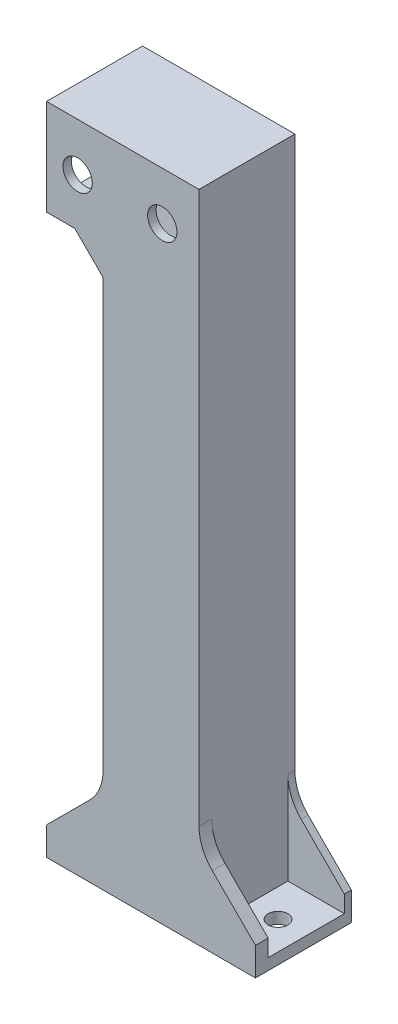
SolidWorks part; units mm, degrees
ref_plane "Front Plane" through (0, 0, 0) normal (0, 0, 1) x (1, 0, 0)
ref_plane "Top Plane" through (0, 0, 0) normal (0, 1, 0) x (1, 0, 0)
ref_plane "Right Plane" through (0, 0, 0) normal (1, 0, 0) x (0, 0, -1)
sketch "Sketch1" plane through (0, 0, 0) normal (0, 0, 1) x (1, 0, 0)
  line L0 (0, 18.3137) -> (0, 94)
  line L2 (17, 0) -> (0, 0)
  line L5 (27, 5) -> (27, 0)
  line L6 (27, 0) -> (17, 0)
  line L8 (-10, 5) -> (-10, 0)
  line L9 (-10, 0) -> (0, 0)
  line L10 (-2.3431, 12.6569) -> (-10, 5)
  line L11 (19.3431, 12.6569) -> (27, 5)
  line L12 (8.5, 0) -> (8.5, 116) construction
  line L13 (-5, 99) -> (-10, 99)
  line L14 (17, 116) -> (-10, 116)
  line L17 (-10, 116) -> (-10, 99)
  line L18 (-5, 99) -> (0, 94)
  line L19 (17, 116) -> (17, 18.3137)
  arc A0 (0, 18.3137) -> (-2.3431, 12.6569) centre (-8, 18.3137) cw
  arc A1 (17, 18.3137) -> (19.3431, 12.6569) centre (25, 18.3137) ccw
  point P19 (0, 0)
  dimension "D3" = 8
  dimension "D6" = 10
  dimension "D7" = 7.6569
  dimension "D10" = 5
  dimension "D1" = 116
  dimension "D2" = 17
  dimension "D4" = 5.6569
  dimension "D5" = 5
  dimension "D8" = 17
  dimension "D9" = 27
  dimension "D11" = 5
extrude "Base Shape" add sketch "Sketch1" along normal blind 17
ref_plane "Plane1" through (0, 2, 0) normal (0, -1, 0) x (-1, 0, 0)
sketch "Sketch4" plane through (0, 2, 0) normal (0, -1, 0) x (-1, 0, 0)
  line L1 (10, -1.25) -> (0, -1.25)
  line L2 (10, -1.25) -> (10, -14.75)
  line L3 (10, -14.75) -> (0, -14.75)
  line L4 (0, -1.25) -> (0, -14.75)
  line L5 (2.3431, 0) -> (10, 0) construction
  line L9 (10, -17) -> (10, 0) construction
  line L10 (10, -17) -> (10, 0) construction
  dimension "D1" = 13.5
  dimension "D2" = 10
  dimension "D3" = 1.25
  dimension "D4" = 0
extrude "Wing Cut Outs" cut sketch "Sketch4" against normal blind 16.5
sketch "Sketch5" plane through (0, 2, 0) normal (0, -1, 0) x (-1, 0, 0)
  line L4 (0, -14.75) -> (10, -14.75) construction
  line L5 (5, -14.75) -> (5, -1.25) construction
  line L6 (10, -1.25) -> (0, -1.25) construction
  line L7 (10, -8) -> (0, -8) construction
  line L8 (10, -14.75) -> (10, -1.25) construction
  line L9 (0, -1.25) -> (0, -14.75) construction
  circle A0 centre (5, -8) radius 1.75
  dimension "D2" = 6.75
  dimension "D1" = 3.5
extrude "Wing Holes" cut sketch "Sketch5" along normal through all
ref_plane "Plane2" through (8.5, 0, 0) normal (1, 0, 0) x (0, 0, -1)
mirror "Mirror1" about plane through (8.5, 0, 0) normal (1, 0, 0) of "Wing Cut Outs"
mirror "Mirror2" about plane through (8.5, 0, 0) normal (1, 0, 0) of "Wing Holes"
sketch "Sketch7" plane through (0, 0, 0) normal (0, 1, 0) x (1, 0, 0)
  line L0 (-10, -17) -> (-10, 0) construction
  line L1 (1.5, -15.5) -> (15.5, -15.5)
  line L2 (1.5, -15.5) -> (1.5, -1.5)
  line L3 (1.5, -1.5) -> (15.5, -1.5)
  line L4 (15.5, -15.5) -> (15.5, -1.5)
  line L5 (-10, 0) -> (27, 0) construction
  dimension "D1" = 11.5
  dimension "D2" = 14
  dimension "D3" = 1.5
extrude "Cut-Extrude1" cut sketch "Sketch7" along normal blind 114.5
ref_plane "Plane3" through (-10, 0, 0) normal (1, 0, 0) x (0, 0, -1)
sketch "Sketch8" plane through (-10, 0, 0) normal (1, 0, 0) x (0, 0, -1)
  line L0 (0, 116) -> (0, 99) construction
  line L1 (-1.5, 114.5) -> (-15.5, 114.5)
  line L2 (-1.5, 114.5) -> (-1.5, 100.5)
  line L3 (-1.5, 100.5) -> (-15.5, 100.5)
  line L4 (-15.5, 114.5) -> (-15.5, 100.5)
  line L5 (-17, 99) -> (0, 99) construction
  dimension "D1" = 14
  dimension "D2" = 1.5
  dimension "D3" = 1.5
extrude "Cut-Extrude2" cut sketch "Sketch8" along normal blind 25.5
ref_plane "Plane4" through (0, 0, 1.5) normal (0, 0, 1) x (1, 0, 0)
sketch "Sketch9" plane through (0, 0, 1.5) normal (0, 0, 1) x (1, 0, 0)
  line L0 (1.5, 94.6213) -> (-4.3787, 100.5)
  line L1 (1.5, 100.5) -> (1.5, 94.6213)
  line L2 (1.5, 100.5) -> (-4.3787, 100.5)
  line L3 (-5, 99) -> (0, 94) construction
  line L4 (-10, 99) -> (-5, 99) construction
  line L5 (0, 94) -> (0, 18.3137) construction
  dimension "D1" = 1.5
  dimension "D2" = 1.5
  dimension "D3" = 1.5
extrude "Cut-Extrude3" cut sketch "Sketch9" along normal blind 14
sketch "Sketch10" plane through (0, 0, 0) normal (0, 0, 1) x (1, 0, 0)
  line L1 (17, 116) -> (-10, 116) construction
  line L2 (17, 18.3137) -> (17, 116) construction
  circle A0 centre (10.5, 107.5) radius 2.6
  circle A1 centre (-4.5, 107.5) radius 2.6
  point P4 (-3.9799, 109.2902)
  point P5 (11.3034, 109.2902)
  dimension "D1" = 5.2
  dimension "D2" = 6.5
  dimension "D3" = 15
  dimension "D4" = 8.5
extrude "Cut-Extrude4" cut sketch "Sketch10" along normal through all
